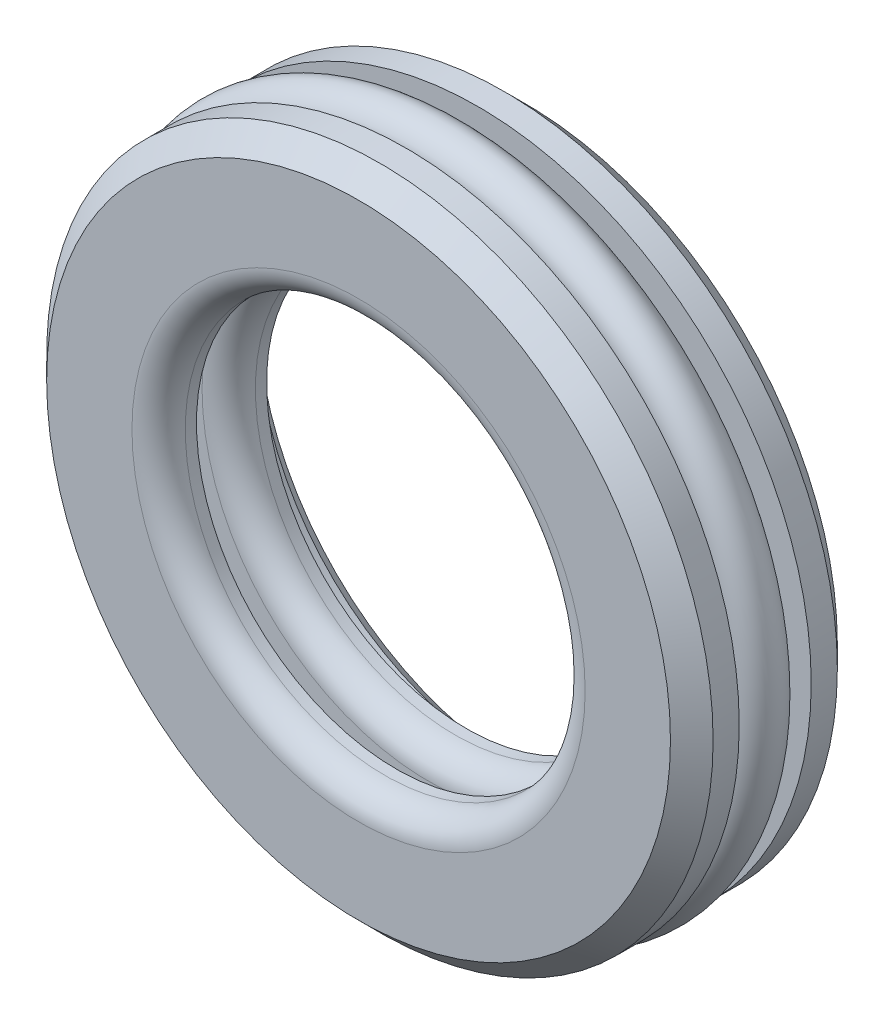
SolidWorks part; units mm, degrees
ref_plane "Front" through (0, 0, 0) normal (0, 0, 1) x (1, 0, 0)
ref_plane "Top" through (0, 0, 0) normal (0, 1, 0) x (1, 0, 0)
ref_plane "Right" through (0, 0, 0) normal (1, 0, 0) x (0, 0, -1)
sketch "Sketch1" plane through (0, 0, 0) normal (1, 0, 0) x (0, 0, -1)
  line L0 (-3.9751, 0) -> (3.9751, 0) construction
  line L1 (105.8582, 289.375) -> (545.1916, 289.375) construction
  line L2 (105.8582, 283.3552) -> (545.1916, 283.3552) construction
  line L3 (-3.9751, 9.525) -> (3.9751, 9.525) construction
  line L4 (-3.9751, 0) -> (-3.9751, 9.525) construction
  line L5 (3.9751, 9.525) -> (3.9751, 0) construction
  line L6 (-2.9591, 15.875) -> (-3.9751, 14.859)
  line L7 (-3.9751, 14.859) -> (-3.9751, 10.795)
  line L8 (-2.9591, 15.875) -> (-1.7145, 15.875)
  line L9 (-1.7145, 15.875) -> (-1.7145, 14.4526)
  line L10 (-1.0795, 13.8176) -> (1.0795, 13.8176)
  line L11 (0, 0) -> (0, 13.8176) construction
  line L12 (-2.7051, 9.525) -> (-2.1717, 9.525)
  line L13 (-2.1717, 9.525) -> (-2.1717, 10.16)
  line L14 (-2.1717, 10.16) -> (-2.7051, 10.16)
  line L15 (-3.3401, 10.795) -> (-3.3401, 11.7475)
  line L16 (2.9591, 15.875) -> (3.9751, 14.859)
  line L17 (2.9591, 15.875) -> (1.7145, 15.875)
  line L18 (1.7145, 15.875) -> (1.7145, 14.4526)
  line L19 (3.9751, 14.859) -> (3.9751, 12.7635)
  line L20 (3.9751, 12.7635) -> (3.2131, 12.0015)
  line L21 (3.2131, 12.0015) -> (0.254, 12.0015)
  line L22 (0, 11.7475) -> (0, 10.795)
  line L23 (0.635, 10.16) -> (1.1684, 10.16)
  line L24 (1.1684, 10.16) -> (1.1684, 9.525)
  line L25 (1.1684, 9.525) -> (0.635, 9.525)
  line L26 (-0.635, 10.795) -> (-0.635, 11.7475)
  line L27 (-0.889, 12.0015) -> (-3.0861, 12.0015)
  arc A0 (-3.9751, 10.795) -> (-2.7051, 9.525) centre (-2.7051, 10.795) ccw
  arc A1 (-2.7051, 10.16) -> (-3.3401, 10.795) centre (-2.7051, 10.795) cw
  circle A2 centre (0, 14.9606) radius 1.143 construction
  arc A3 (-1.7145, 14.4526) -> (-1.0795, 13.8176) centre (-1.0795, 14.4526) ccw
  arc A4 (1.7145, 14.4526) -> (1.0795, 13.8176) centre (1.0795, 14.4526) cw
  arc A5 (0.635, 9.525) -> (-0.635, 10.795) centre (0.635, 10.795) cw
  arc A6 (0, 10.795) -> (0.635, 10.16) centre (0.635, 10.795) ccw
  arc A7 (0.254, 12.0015) -> (0, 11.7475) centre (0.254, 11.7475) ccw
  arc A8 (-0.635, 11.7475) -> (-0.889, 12.0015) centre (-0.889, 11.7475) ccw
  arc A9 (-3.3401, 11.7475) -> (-3.0861, 12.0015) centre (-3.0861, 11.7475) cw
  point P43 (-0.635, 9.525)
  dimension "D3" = 1.27
  dimension "D4" = 0.635
  dimension "D9" = 2.286
  dimension "D10" = 0.635
  dimension "D14" = 0.254
  dimension "SealWidth" = 7.9502
  dimension "SealID" = 19.05
  dimension "SealOD" = 31.75
  dimension "D5" = 45
  dimension "D6" = 1.016
  dimension "D7" = 2.2606
  dimension "D8" = 2.0574
  dimension "D11" = 2.4765
  dimension "D12" = 1.8034
  dimension "D13" = 3.3401
  dimension "D15" = 3.1115
revolve "Revolve1" add sketch "Sketch1" angle 360 about L0
sketch "Sketch2" plane through (0, 0, 0) normal (1, 0, 0) x (0, 0, -1)
  line L0 (-3.9751, 0) -> (3.9751, 0) construction
  circle A0 centre (0, 14.9606) radius 1.143
  circle A1 centre (0, 14.9606) radius 1.143 construction
revolve "Revolve2" add sketch "Sketch2" angle 360 about L0
